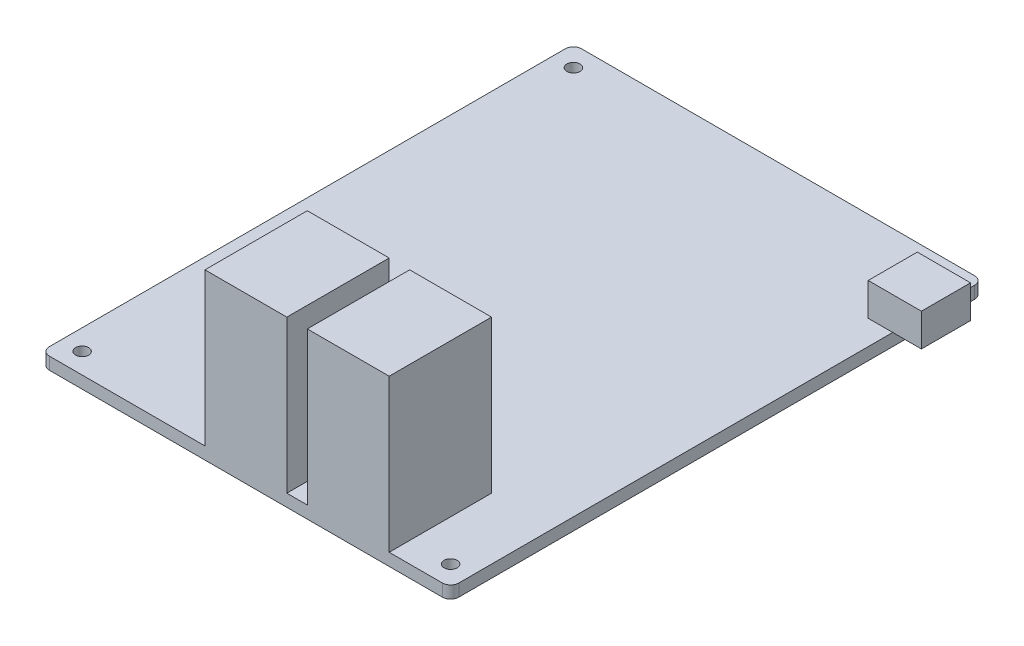
SolidWorks part; units mm, degrees
ref_plane "前视基准面" through (0, 0, 0) normal (0, 0, 1) x (1, 0, 0)
ref_plane "上视基准面" through (0, 0, 0) normal (0, 1, 0) x (1, 0, 0)
ref_plane "右视基准面" through (0, 0, 0) normal (1, 0, 0) x (0, 0, -1)
sketch "草图1" plane through (0, 0, 0) normal (0, 1, 0) x (1, 0, 0)
  line L1 (-50, -65) -> (50, -65)
  line L2 (-50, -65) -> (-50, 65)
  line L3 (-50, 65) -> (50, 65)
  line L4 (50, -65) -> (50, 65)
  line L5 (-50, -65) -> (50, 65) construction
  line L6 (-50, 65) -> (50, -65) construction
  point P0 (0, 0)
  dimension "D1" = 100
  dimension "D2" = 130
extrude "凸台-拉伸1" add sketch "草图1" along normal blind 3 contours L4 L3 L2 L1
sketch "草图2" plane through (0, 3, 0) normal (0, 1, 0) x (1, 0, 0)
  line L1 (-10, -40) -> (10, -40)
  line L2 (-10, -40) -> (-10, -65)
  line L3 (-10, -65) -> (10, -65)
  line L4 (10, -40) -> (10, -65)
  line L5 (-10, -40) -> (10, -65) construction
  line L6 (-10, -65) -> (10, -40) construction
  line L10 (0, 0) -> (0, 50.1662) construction
  line L11 (0, 0) -> (74.4117, 0) construction
  line L12 (15, -40) -> (35, -40)
  line L13 (15, -40) -> (15, -65)
  line L14 (15, -65) -> (35, -65)
  line L15 (35, -40) -> (35, -65)
  line L16 (15, -40) -> (35, -65) construction
  line L17 (15, -65) -> (35, -40) construction
  line L18 (-50, -65) -> (50, -65) construction
  point P0 (0, -52.5)
  point P5 (25, -52.5)
  dimension "D1" = 25
  dimension "D2" = 20
  dimension "D3" = 25
  dimension "D4" = 20
  dimension "D5" = 10
  dimension "D6" = 5
extrude "凸台-拉伸2" add sketch "草图2" along normal blind 37.25
fillet "圆角1" radius 2 4 edges at (-50, 1.5, -65) (50, 1.5, -65) (50, 1.5, 65) (-50, 1.5, 65)
sketch "草图3" plane through (0, 3, 0) normal (0, 1, 0) x (1, 0, 0)
  line L0 (-64.6068, 0) -> (64.6068, 0) construction
  line L1 (44, 55) -> (57, 55)
  line L2 (44, 55) -> (44, 43)
  line L3 (44, 43) -> (57, 43)
  line L4 (57, 55) -> (57, 43)
  line L5 (44, 55) -> (57, 43) construction
  line L6 (44, 43) -> (57, 55) construction
  line L7 (0, -81.0555) -> (0, 81.0555) construction
  line L8 (-48, 65) -> (48, 65) construction
  line L9 (50, -63) -> (50, 63) construction
  point P0 (50.5, 49)
  point P9 (0, 0)
  point P13 (0, 0)
  dimension "D1" = 13
  dimension "D2" = 12
  dimension "D3" = 10
  dimension "D4" = 6
extrude "凸台-拉伸3" add sketch "草图3" along normal blind 8
sketch "草图4" plane through (0, 3, 0) normal (0, 1, 0) x (1, 0, 0)
  line L0 (0, 0) -> (-60.9398, 0) construction
  line L1 (0, 0) -> (0, 86.5603) construction
  line L2 (-48, -65) -> (-10, -65) construction
  line L3 (-50, -63) -> (-50, 63) construction
  circle A0 centre (-45, -60) radius 1.6
  circle A1 centre (-45, 60) radius 1.6
  circle A2 centre (45, 60) radius 1.6
  circle A3 centre (45, -60) radius 1.6
  dimension "D3" = 3.2
  dimension "D1" = 5
  dimension "D2" = 5
extrude "切除-拉伸1" cut sketch "草图4" against normal through all
